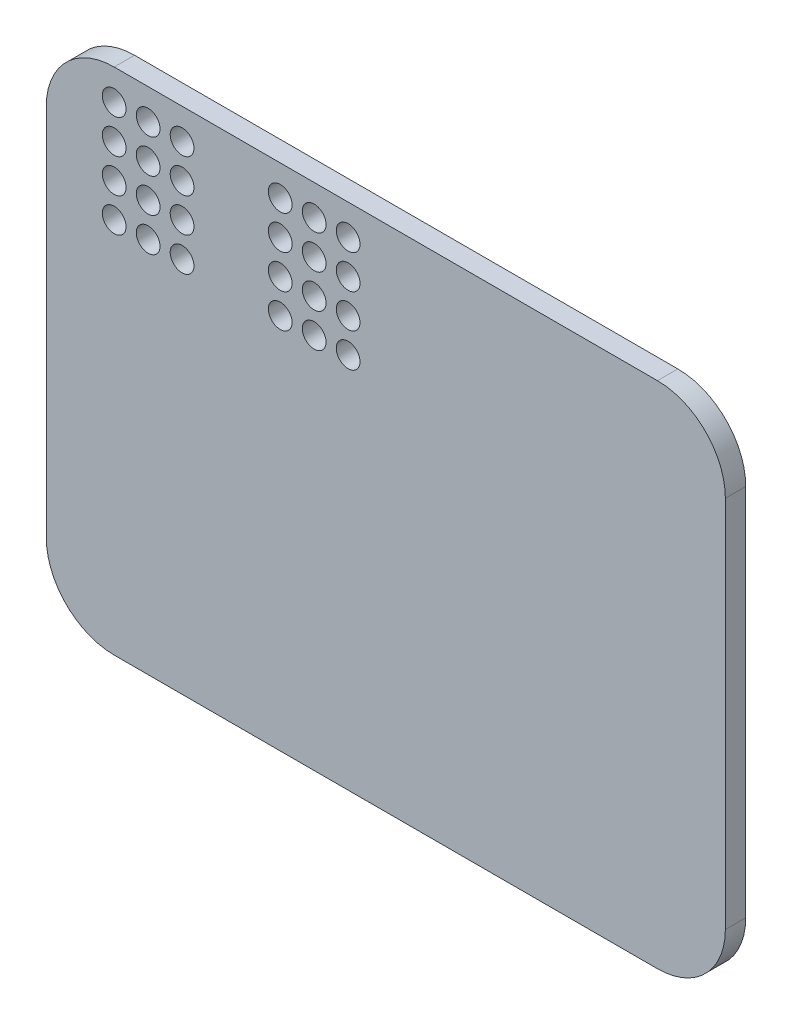
SolidWorks part; units mm, degrees
ref_plane "Front Plane" through (0, 0, 0) normal (0, 0, 1) x (1, 0, 0)
ref_plane "Top Plane" through (0, 0, 0) normal (0, 1, 0) x (1, 0, 0)
ref_plane "Right Plane" through (0, 0, 0) normal (1, 0, 0) x (0, 0, -1)
sketch "Sketch1" plane through (0, 0, 0) normal (0, 0, 1) x (1, 0, 0)
  line L1 (10, 0) -> (90, 0)
  line L2 (0, 10) -> (0, 65)
  line L3 (10, 75) -> (90, 75)
  line L4 (100, 10) -> (100, 65)
  circle A0 centre (10, 70.5) radius 1.75
  circle A1 centre (10, 65.5) radius 1.75
  circle A2 centre (10, 60.5) radius 1.75
  circle A3 centre (10, 55.5) radius 1.75
  circle A4 centre (15, 70.5) radius 1.75
  circle A5 centre (15, 65.5) radius 1.75
  circle A6 centre (15, 60.5) radius 1.75
  circle A7 centre (15, 55.5) radius 1.75
  circle A8 centre (20, 70.5) radius 1.75
  circle A9 centre (20, 65.5) radius 1.75
  circle A10 centre (20, 60.5) radius 1.75
  circle A11 centre (20, 55.5) radius 1.75
  circle A12 centre (34.45, 70.5) radius 1.75
  circle A13 centre (39.45, 70.5) radius 1.75
  circle A14 centre (44.45, 70.5) radius 1.75
  circle A15 centre (44.45, 65.5) radius 1.75
  circle A16 centre (39.45, 65.5) radius 1.75
  circle A17 centre (34.45, 65.5) radius 1.75
  circle A18 centre (34.45, 60.5) radius 1.75
  circle A19 centre (39.45, 60.5) radius 1.75
  circle A20 centre (44.45, 60.5) radius 1.75
  circle A21 centre (44.45, 55.5) radius 1.75
  circle A22 centre (39.45, 55.5) radius 1.75
  circle A23 centre (34.45, 55.5) radius 1.75
  arc A24 (0, 65) -> (10, 75) centre (10, 65) cw
  arc A25 (10, 0) -> (0, 10) centre (10, 10) cw
  arc A26 (90, 0) -> (100, 10) centre (90, 10) ccw
  arc A27 (90, 75) -> (100, 65) centre (90, 65) cw
  point P55 (0, 75)
  point P58 (0, 0)
  point P63 (100, 75)
  dimension "D1" = 3.5
  dimension "D2" = 4.5
  dimension "D4" = 10
  dimension "D6" = 5
  dimension "D7" = 5
  dimension "D11" = 24.45
  dimension "D12" = 10
  dimension "D9" = 75
  dimension "D10" = 100
  dimension "D3" = 4
  dimension "D5" = 3
  dimension "D8" = 2
extrude "Boss-Extrude1" add sketch "Sketch1" along normal blind 3
